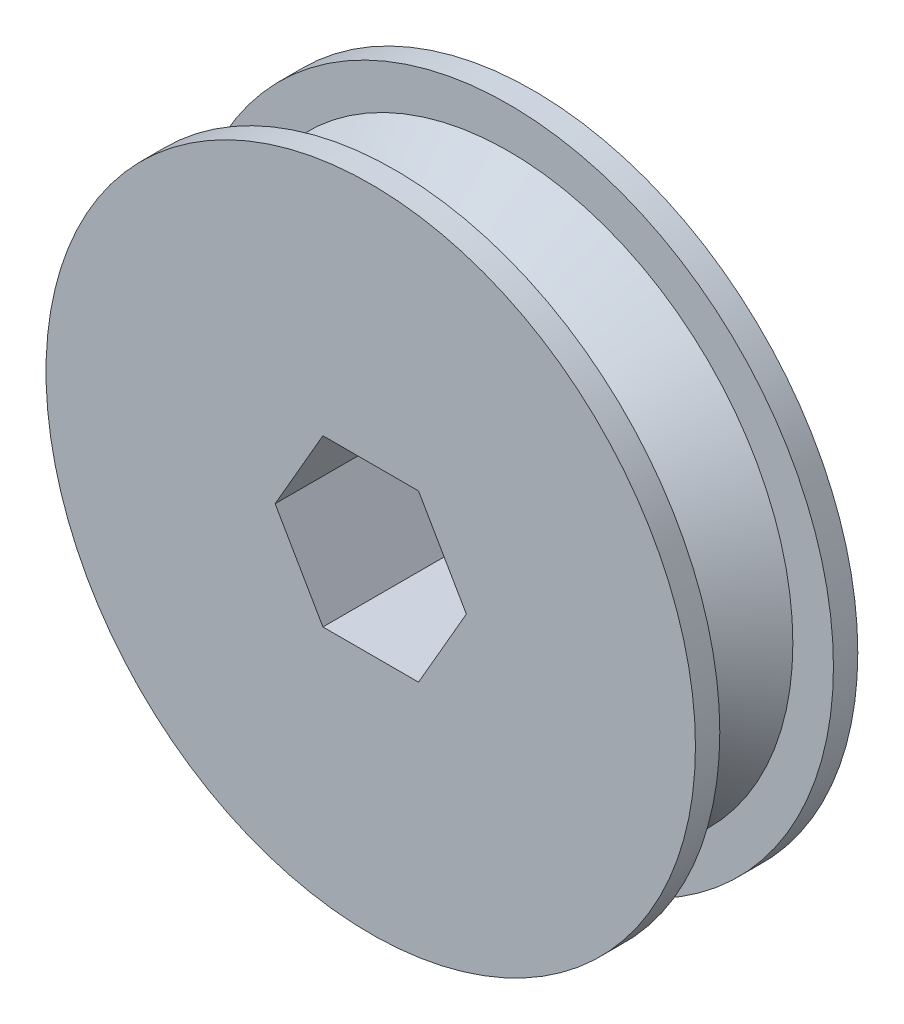
SolidWorks part; units mm, degrees
material "PPE"
ref_plane "Front Plane" through (0, 0, 0) normal (0, 0, 1) x (1, 0, 0)
ref_plane "Top Plane" through (0, 0, 0) normal (0, 1, 0) x (1, 0, 0)
ref_plane "Right Plane" through (0, 0, 0) normal (1, 0, 0) x (0, 0, -1)
sketch "Sketch1" plane through (0, 0, 0) normal (0, 0, 1) x (1, 0, 0)
  circle A0 centre (0, 0) radius 25.4
  dimension "D1" = 50.8
extrude "Boss-Extrude1" add sketch "Sketch1" along normal mid plane 12.7
sketch "Sketch3" plane through (0, 0, 0) normal (0, 1, 0) x (1, 0, 0)
  line L0 (-25.4, 6.35) -> (-25.4, -6.35) construction
  line L1 (-25.4, 4.445) -> (-25.4, -4.445)
  line L2 (-22.225, 4.445) -> (-25.4, 4.445)
  line L3 (-22.225, -4.445) -> (-25.4, -4.445)
  line L4 (-22.225, -4.445) -> (-17.78, 0)
  line L5 (-17.78, 0) -> (-22.225, 4.445)
  line L6 (-25.4, -6.35) -> (25.4, -6.35) construction
  dimension "D1" = 8.89
  dimension "D2" = 3.175
  dimension "D3" = 4.445
  dimension "D4" = 4.445
  dimension "D5" = 3.175
  dimension "D6" = 1.905
ref_axis "Axis1" through (0, 0, 17.1197) along (0, 0, -1)
revolve "Cut-Revolve1" cut sketch "Sketch3" angle 360 about axis through (0, 0, 17.1197) along (0, 0, -1)
sketch "Sketch4" plane through (0, 0, -6.35) normal (0, 0, -1) x (-1, 0, 0)
  line L0 (7.479, 0) -> (3.7395, 6.477)
  line L1 (3.7395, 6.477) -> (-3.7395, 6.477)
  line L2 (-3.7395, 6.477) -> (-7.479, 0)
  line L3 (-7.479, 0) -> (-3.7395, -6.477)
  line L4 (-3.7395, -6.477) -> (3.7395, -6.477)
  line L5 (3.7395, -6.477) -> (7.479, 0)
  point P2 (0, 6.477)
  dimension "D1" = 12.954
  dimension "D2" = 12.954
  dimension "D3" = 12.954
  dimension "D4" = 6.477
  dimension "D5" = 120
extrude "Cut-Extrude1" cut sketch "Sketch4" against normal through all
